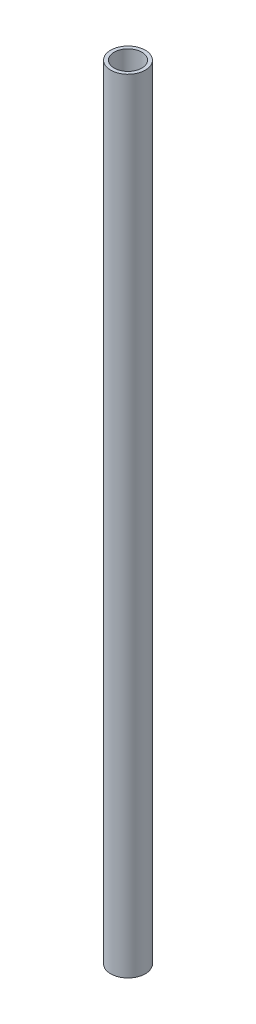
SolidWorks part; units mm, degrees
ref_plane "Front Plane" through (0, 0, 0) normal (0, 0, 1) x (1, 0, 0)
ref_plane "Top Plane" through (0, 0, 0) normal (0, 1, 0) x (1, 0, 0)
ref_plane "Right Plane" through (0, 0, 0) normal (1, 0, 0) x (0, 0, -1)
sketch "Sketch1" plane through (0, 0, 0) normal (0, 1, 0) x (1, 0, 0)
  circle A0 centre (0, 0) radius 10
  circle A1 centre (0, 0) radius 8
  dimension "D1" = 20
extrude "Boss-Extrude1" add sketch "Sketch1" along normal blind 452
